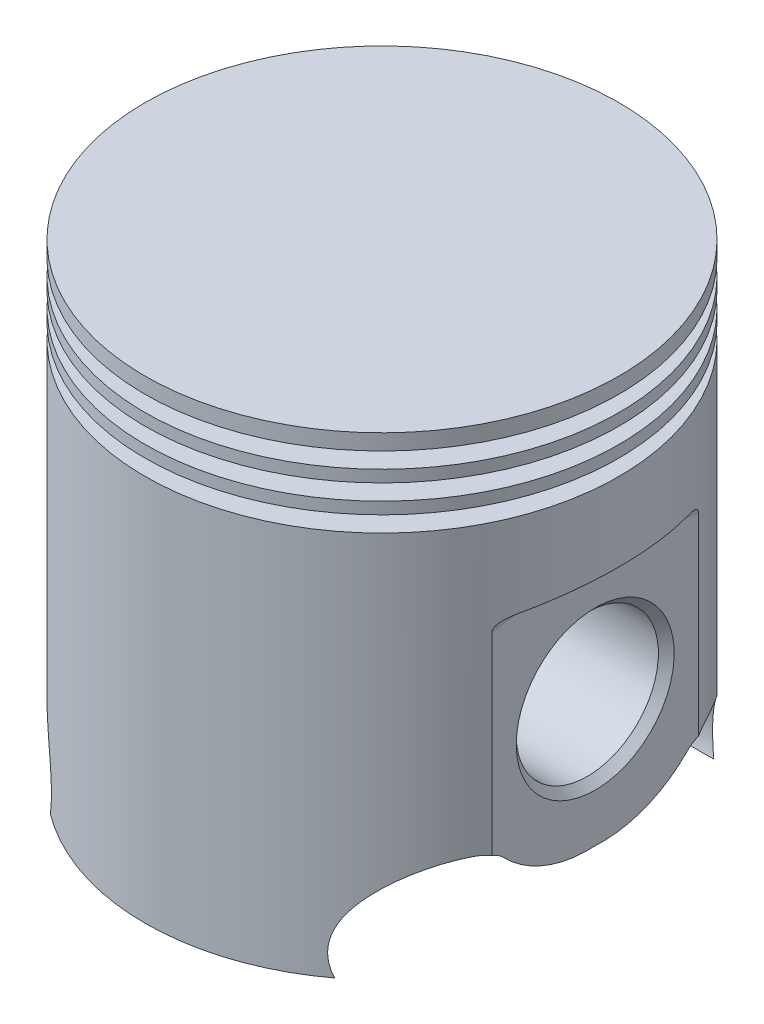
SolidWorks part; units mm, degrees
ref_plane "Front Plane" through (0, 0, 0) normal (0, 0, 1) x (1, 0, 0)
ref_plane "Top Plane" through (0, 0, 0) normal (0, 1, 0) x (1, 0, 0)
ref_plane "Right Plane" through (0, 0, 0) normal (1, 0, 0) x (0, 0, -1)
sketch "Sketch1" plane through (0, 0, 0) normal (0, 0, 1) x (1, 0, 0)
  line L0 (25.5, 0) -> (30, 0)
  line L1 (30, 0) -> (30, 49)
  line L2 (30, 49) -> (25.52, 49)
  line L3 (25.52, 49) -> (25.52, 51)
  line L4 (25.52, 51) -> (30, 51)
  line L5 (30, 51) -> (30, 52.5)
  line L6 (30, 52.5) -> (25.52, 52.5)
  line L7 (25.52, 52.5) -> (25.52, 54.5)
  line L8 (25.52, 54.5) -> (30, 54.5)
  line L9 (30, 54.5) -> (30, 56)
  line L10 (30, 56) -> (25.52, 56)
  line L11 (25.52, 56) -> (25.52, 58)
  line L12 (25.52, 58) -> (30, 58)
  line L13 (30, 58) -> (30, 60)
  line L14 (30, 60) -> (0, 60)
  line L15 (0, 60) -> (0, 51)
  line L16 (0, 51) -> (22.02, 51)
  line L17 (22.02, 51) -> (22.02, 21.56)
  line L19 (25.5, 6) -> (25.5, 0)
  line L21 (25.5, 6) -> (20.02, 10.5983)
  line L22 (20.02, 10.5983) -> (20.02, 19.8818)
  line L23 (20.02, 19.8818) -> (22.02, 21.56)
  dimension "D1" = 60
  dimension "D2" = 2
  dimension "D3" = 2
  dimension "D4" = 2
  dimension "D5" = 2
  dimension "D6" = 1.5
  dimension "D7" = 1.5
  dimension "D8" = 30
  dimension "D11" = 6
  dimension "D10" = 130
  dimension "D9" = 4.5
  dimension "D12" = 25.52
  dimension "D13" = 22.02
  dimension "D14" = 21.56
  dimension "D15" = 130
  dimension "D16" = 2
revolve "Revolve1" add sketch "Sketch1" angle 360 about L15
ref_plane "Plane1" through (10, 0, 0) normal (1, 0, 0) x (0, 0, -1)
sketch "Sketch2" plane through (10, 0, 0) normal (1, 0, 0) x (0, 0, -1)
  circle A0 centre (0, 23.1) radius 12.5
  dimension "D1" = 25
  dimension "D2" = 23.1
extrude "Boss-Extrude1" add sketch "Sketch2" along normal up to surface (8.1282 mm away)
sketch "Sketch3" plane through (10, 0, 0) normal (-1, 0, 0) x (0, 0, 1)
  circle A0 centre (0, 23.1) radius 9
  dimension "D1" = 18
extrude "Cut-Extrude1" cut sketch "Sketch3" against normal through all
ref_plane "Plane2" through (30.01, 0, 0) normal (1, 0, 0) x (0, 0, -1)
sketch "Sketch4" plane through (30.01, 0, 0) normal (1, 0, 0) x (0, 0, -1)
  line L0 (-30, 0) -> (30, 0) construction
  line L1 (-13.075, 0) -> (13.075, 0)
  line L2 (-13.075, 0) -> (-13.075, 38)
  line L4 (13.075, 0) -> (13.075, 38)
  arc A0 (-13.075, 38) -> (13.075, 38) centre (0, -40.9243) cw
  dimension "D3" = 80
  dimension "D1" = 26.15
  dimension "D2" = 13.075
  dimension "D4" = 38
extrude "Cut-Extrude2" cut sketch "Sketch4" against normal blind 3.01
chamfer "Chamfer1" distance 1 angle 45 1 edges at (27, 23.1, 9)
sketch "Sketch14" plane through (30.01, 0, 0) normal (1, 0, 0) x (0, 0, -1)
  line L0 (-30, 0) -> (30, 0) construction
  line L1 (30, 49) -> (-30, 49) construction
  line L2 (0, 13.2974) -> (0, -7.8708) construction
  line L3 (-24, 0) -> (24, 0)
  arc A0 (-24, 0) -> (-14.5555, 12.7265) centre (-14.365, 2.7174) cw
  arc A1 (-11.6121, 11.5163) -> (0, 7) centre (-0.86, 21.9753) ccw
  arc A2 (-14.5555, 12.7265) -> (-11.6121, 11.5163) centre (-14.4794, 8.7272) cw
  arc A3 (24, 0) -> (14.5555, 12.7265) centre (14.365, 2.7174) ccw
  arc A4 (14.5555, 12.7265) -> (11.6121, 11.5163) centre (14.4794, 8.7272) ccw
  arc A5 (11.6121, 11.5163) -> (0, 7) centre (0.86, 21.9753) cw
  point P9 (-12.537, 12.56)
  dimension "D1" = 12.56
  dimension "D2" = 4
  dimension "D3" = 15
  dimension "D4" = 6
  dimension "D5" = 42
extrude "Cut-Extrude3" cut sketch "Sketch14" against normal through all
mirror "Mirror1" about plane through (0, 0, 0) normal (1, 0, 0) of "Boss-Extrude1", "Cut-Extrude1", "Chamfer1", "Cut-Extrude2"
fillet "Fillet2" radius 1 2 edges at (27, 39.0757, 0) (-27, 39.0757, 0)
sketch "Sketch15" plane through (0, 60, 0) normal (0, 1, 0) x (1, 0, 0)
  line L0 (30, 0) -> (-30, 0) construction
  circle A0 centre (0, 0) radius 30 construction
  circle A1 centre (15, 0) radius 4
  circle A2 centre (-15, 0) radius 4
  dimension "D1" = 15
  dimension "D3" = 8
  dimension "D4" = 8
  dimension "D2" = 15
